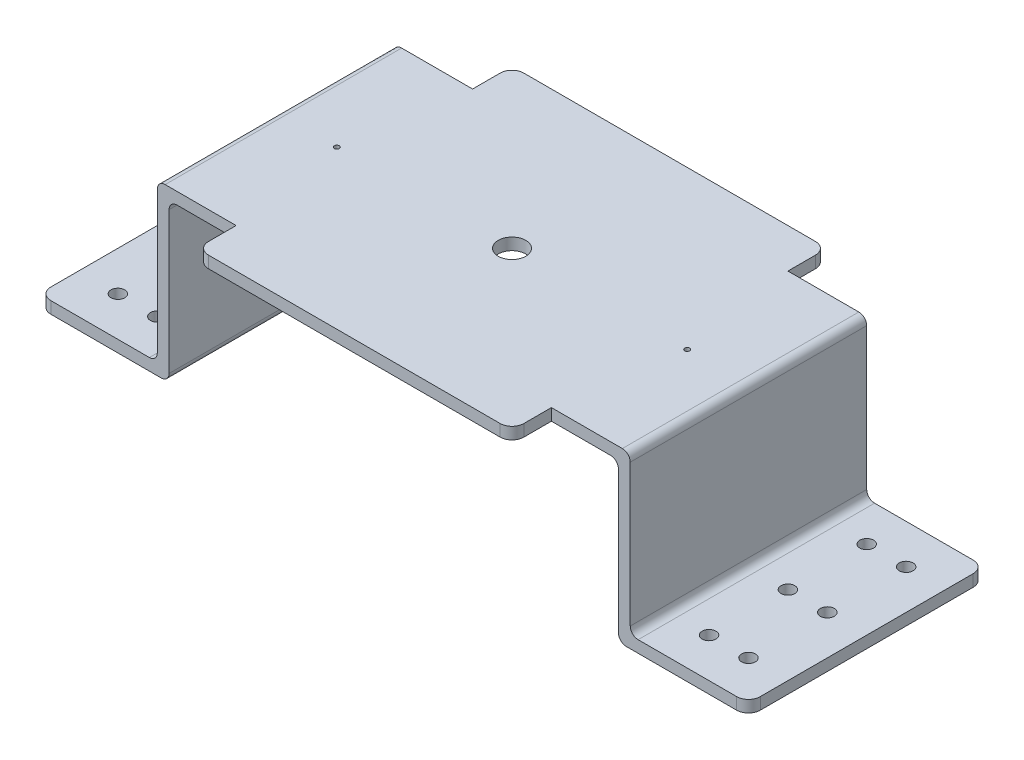
SolidWorks part; units mm, degrees
ref_plane "Front" through (0, 0, 0) normal (0, 0, 1) x (1, 0, 0)
ref_plane "Top" through (0, 0, 0) normal (0, 1, 0) x (1, 0, 0)
ref_plane "Right" through (0, 0, 0) normal (1, 0, 0) x (0, 0, -1)
sketch "草图1" plane through (0, 0, 0) normal (0, 1, 0) x (1, 0, 0)
  line L1 (-60, 30) -> (60, 30)
  line L2 (-60, 30) -> (-60, -30)
  line L3 (-60, -30) -> (60, -30)
  line L4 (60, 30) -> (60, -30)
  line L5 (-60, 30) -> (60, -30) construction
  line L6 (-60, -30) -> (60, 30) construction
  point P0 (0, 0)
  dimension "D1" = 60
  dimension "D2" = 120
extrude "凸台-拉伸1" add sketch "草图1" along normal blind 3 contours L1 L4 L3 L2
sketch "草图2" plane through (0, 0, 0) normal (0, -1, 0) x (1, 0, 0)
  line L0 (-60, -30) -> (60, -30) construction
  line L1 (-60, 30) -> (-57, 30)
  line L2 (-60, 30) -> (-60, -30)
  line L3 (-60, -30) -> (-57, -30)
  line L4 (-57, 30) -> (-57, -30)
  dimension "D1" = 3
extrude "凸台-拉伸2" add sketch "草图2" along normal blind 40
sketch "草图3" plane through (-60, 0, 0) normal (-1, 0, 0) x (0, 0, 1)
  line L0 (30, 3) -> (30, -40) construction
  line L1 (-30, -40) -> (30, -40)
  line L2 (-30, -40) -> (-30, -37)
  line L3 (-30, -37) -> (30, -37)
  line L4 (30, -40) -> (30, -37)
  dimension "D1" = 3
extrude "凸台-拉伸3" add sketch "草图3" along normal blind 30
sketch "草图4" plane through (0, -37, 0) normal (0, 1, 0) x (1, 0, 0)
  line L0 (-90, -30) -> (-60, -30) construction
  line L1 (0, -50) -> (0, 50) construction
  circle A0 centre (-70, -20) radius 1.75
  dimension "D1" = 3.5
  dimension "D2" = 10
  dimension "D3" = 70
extrude "切除-拉伸1" cut sketch "草图4" against normal blind 3
pattern_linear "阵列(线性)1" count 3 spacing 20 along (0, 0, -1) count 2 spacing 10 along (-1, 0, 0) of "切除-拉伸1"
mirror "镜向1" about plane through (0, 0, 0) normal (1, 0, 0) of "阵列(线性)1", "凸台-拉伸3", "凸台-拉伸2", "切除-拉伸1"
sketch "草图5" plane through (0, 3, 0) normal (0, 1, 0) x (1, 0, 0)
  circle A0 centre (0, 0) radius 3.5
  dimension "D1" = 7
extrude "切除-拉伸2" cut sketch "草图5" against normal blind 3
sketch "草图6" plane through (0, 3, 0) normal (0, 1, 0) x (1, 0, 0)
  circle A0 centre (44.45, 0) radius 0.5
  circle A1 centre (0, 0) radius 3.5 construction
  dimension "D1" = 1
  dimension "D2" = 44.45
extrude "切除-拉伸3" cut sketch "草图6" against normal blind 3
mirror "镜向2" about plane through (0, 0, 0) normal (1, 0, 0) of "切除-拉伸3"
sketch "草图7" plane through (0, 3, 0) normal (0, 1, 0) x (1, 0, 0)
  line L0 (-60, 30) -> (60, 30) construction
  line L1 (-40, 30) -> (40, 30)
  line L2 (-40, 30) -> (-40, 40)
  line L3 (-40, 40) -> (40, 40)
  line L4 (40, 30) -> (40, 40)
  circle A0 centre (0, 0) radius 3.5 construction
  dimension "D1" = 40
  dimension "D2" = 40
  dimension "D3" = 40
extrude "凸台-拉伸4" add sketch "草图7" against normal blind 3
mirror "镜向3" about plane through (0, 0, 0) normal (0, 0, 1) of "凸台-拉伸4"
fillet "圆角1" radius 3 1 edges at (-40, 1.5, 40)
fillet "圆角2" radius 3 3 edges at (40, 1.5, 40) (40, 1.5, -40) (-40, 1.5, -40)
hole_wizard "M1.6 螺纹孔1" positions "草图11" profile "草图10" tap size "M1.6" standard "GB" end condition through all
sketch "草图11" plane through (0, 3, 0) normal (0, 1, 0) x (1, 0, 0)
  point P0 (44.45, 0)
  point P3 (-44.45, 0)
sketch "草图10" plane through (44.45, 3, 0) normal (1, 0, 0) x (0, 0, 1)
  line L0 (0, 0) -> (0, 43)
  line L1 (0, 43) -> (0.625, 43)
  line L2 (0.625, 43) -> (0.625, 0)
  line L5 (0.625, 0) -> (0, 0)
  line L11 (0, -6.35) -> (0, 107.95) construction
  dimension "通孔螺纹孔钻头直径" = 1.25
  dimension "通孔螺纹孔钻头深度" = 43
cosmetic thread "孔螺蚊线1" parameters "D2"=1.6
cosmetic thread "孔螺蚊线2" parameters "D2"=1.6
fillet "圆角3" radius 2 2 edges at (-57, 0, 0) (-60, 3, 0)
fillet "圆角4" radius 2 6 edges at (-57, -40, 0) (-60, -37, 0) (60, -37, 0) (57, -40, 0) (57, 0, 0) (60, 3, 0)
fillet "圆角5" radius 3 4 edges at (-90, -38.5, -30) (-90, -38.5, 30) (90, -38.5, -30) (90, -38.5, 30)
